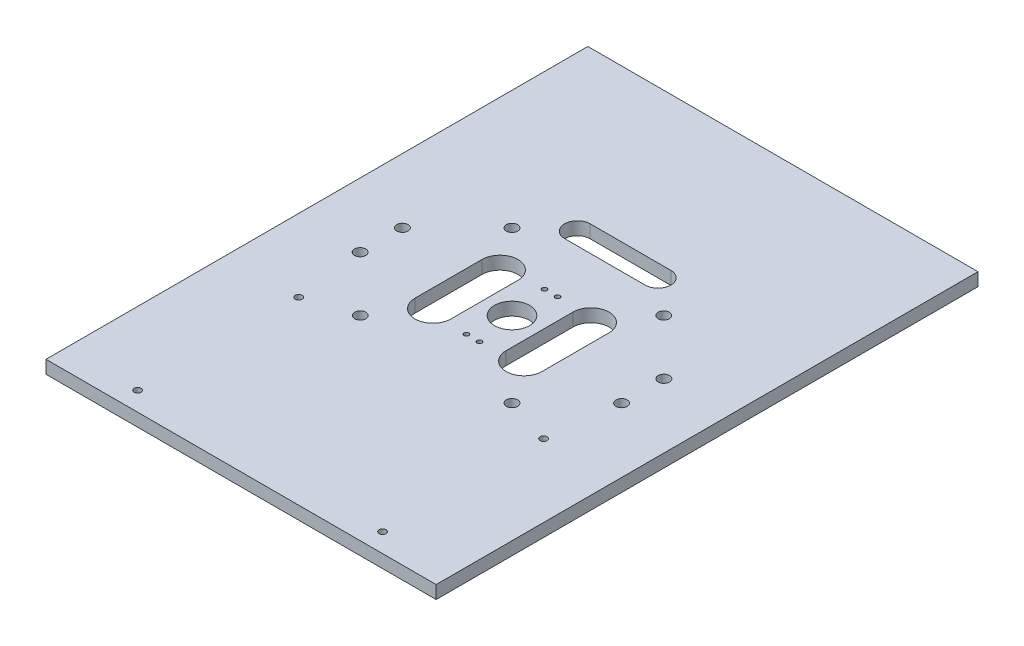
SolidWorks part; units mm, degrees
ref_plane "前视基准面" through (0, 0, 0) normal (0, 0, 1) x (1, 0, 0)
ref_plane "上视基准面" through (0, 0, 0) normal (0, 1, 0) x (1, 0, 0)
ref_plane "右视基准面" through (0, 0, 0) normal (1, 0, 0) x (0, 0, -1)
other "Configuration Table"
sketch "草图1" plane through (0, 0, 0) normal (0, 1, 0) x (1, 0, 0)
  line L1 (40, 40) -> (-40, 40)
  line L2 (40, 40) -> (40, -40)
  line L3 (40, -40) -> (-40, -40)
  line L4 (-40, 40) -> (-40, -40)
  line L5 (40, 40) -> (-40, -40) construction
  line L6 (40, -40) -> (-40, 40) construction
  point P0 (0, 0)
extrude "凸台-拉伸1" add sketch "草图1" along normal blind 2
sketch "草图2" plane through (0, 2, 0) normal (0, 1, 0) x (1, 0, 0)
  line L0 (-40, 40) -> (-33, 40)
  line L1 (40, 40) -> (-40, 40) construction
  line L2 (-40, 40) -> (-40, 33)
  line L3 (-40, 40) -> (-40, -40) construction
  line L4 (40, 40) -> (33, 40)
  line L5 (-40, -40) -> (-40, -33)
  circle A0 centre (-33, 33) radius 2.5
  circle A1 centre (33, 33.941) radius 2.5
  circle A2 centre (-33, -33) radius 2.5
  circle A3 centre (33, -33) radius 2.5
extrude "切除-拉伸1" cut sketch "草图2" against normal blind 2 contours A2 | A0 | A1 | A3
sketch "草图3" plane through (0, 0, 0) normal (0, -1, 0) x (1, 0, 0)
  circle A0 centre (-2.5, 17.5) radius 1
  circle A1 centre (2.5, 17.5) radius 1
  circle A2 centre (-2.5, -17.5) radius 1
  circle A4 centre (2.5, -17.5) radius 1
  point P4 (0, 0)
  point P8 (0, 17.5)
extrude "切除-拉伸2" cut sketch "草图3" against normal blind 2
sketch "草图4" plane through (0, 0, 0) normal (0, -1, 0) x (1, 0, 0)
  circle A0 centre (0, 0) radius 8
extrude "切除-拉伸3" cut sketch "草图4" against normal blind 2
sketch "草图5" plane through (0, 0, 0) normal (0, -1, 0) x (1, 0, 0)
  circle A0 centre (33, 33) radius 2.6
  circle A1 centre (33, -33.941) radius 2.6
  circle A2 centre (-33, -33) radius 2.6
  circle A3 centre (-33, 33) radius 2.6
  circle A4 centre (-2.5, 17.5) radius 1.1
  circle A5 centre (2.5, 17.5) radius 1.1
  circle A6 centre (2.5, -17.5) radius 1.1
  circle A7 centre (-2.5, -17.5) radius 1.1
  dimension "D1" = 5.2
  dimension "D2" = 5.2
  dimension "D3" = 5.2
  dimension "D4" = 5.2
extrude "切除-拉伸4" cut sketch "草图5" against normal blind 10
sketch "草图6" plane through (0, 0, 0) normal (0, -1, 0) x (1, 0, 0)
  line L0 (10.3007, -26.4641) -> (-10.3007, -26.4641) construction
  line L1 (10.3007, -30.5356) -> (-10.3007, -30.5356)
  line L2 (10.3007, -22.3927) -> (-10.3007, -22.3927)
  arc A0 (10.3007, -30.5356) -> (10.3007, -22.3927) centre (10.3007, -26.4641) ccw
  arc A1 (-10.3007, -22.3927) -> (-10.3007, -30.5356) centre (-10.3007, -26.4641) ccw
  point P2 (0, -26.4641)
extrude "切除-拉伸5" cut sketch "草图6" against normal blind 10
sketch "草图7" plane through (0, 0, 0) normal (0, -1, 0) x (1, 0, 0)
  line L1 (62.5, 62.5) -> (-62.5, 62.5)
  line L2 (62.5, 62.5) -> (62.5, -62.5)
  line L3 (62.5, -62.5) -> (-62.5, -62.5)
  line L4 (-62.5, 62.5) -> (-62.5, -62.5)
  line L5 (62.5, 62.5) -> (-62.5, -62.5) construction
  line L6 (62.5, -62.5) -> (-62.5, 62.5) construction
  line L8 (-10.3007, -30.5356) -> (10.3007, -30.5356)
  line L9 (10.3007, -22.3927) -> (-10.3007, -22.3927)
  line L10 (-10.3007, -30.5356) -> (10.3007, -30.5356)
  line L11 (10.3007, -22.3927) -> (-10.3007, -22.3927)
  circle A0 centre (2.5, 17.5) radius 1.1 construction
  circle A1 centre (2.5, 17.5) radius 1.1
  arc A2 (-10.3007, -22.3927) -> (-10.3007, -30.5356) centre (-10.3007, -26.4641) ccw
  arc A3 (10.3007, -30.5356) -> (10.3007, -22.3927) centre (10.3007, -26.4641) ccw
  arc A4 (-10.3007, -22.3927) -> (-10.3007, -30.5356) centre (-10.3007, -26.4641) ccw
  arc A5 (10.3007, -30.5356) -> (10.3007, -22.3927) centre (10.3007, -26.4641) ccw
  circle A6 centre (-2.5, 17.5) radius 1.1 construction
  circle A7 centre (-2.5, 17.5) radius 1.1
  circle A8 centre (-33, -33) radius 2.6 construction
  circle A9 centre (-2.5, -17.5) radius 1.1 construction
  circle A10 centre (2.5, -17.5) radius 1.1 construction
  circle A11 centre (0, 0) radius 8 construction
  circle A12 centre (33, -33.941) radius 2.6 construction
  circle A13 centre (33, 33) radius 2.6 construction
  circle A14 centre (-33, 33) radius 2.6 construction
  circle A15 centre (-33, -33) radius 2.6
  circle A16 centre (-2.5, -17.5) radius 1.1
  circle A17 centre (2.5, -17.5) radius 1.1
  circle A18 centre (0, 0) radius 8
  circle A19 centre (33, -33.941) radius 2.6
  circle A20 centre (33, 33) radius 2.6
  circle A21 centre (-33, 33) radius 2.6
  point P0 (0, 0)
  dimension "D1" = 0
extrude "凸台-拉伸2" add sketch "草图7" against normal blind 2
sketch "草图8" plane through (0, 0, 0) normal (0, -1, 0) x (1, 0, 0)
  line L2 (125, -125) -> (-125, -125)
  line L3 (125, -125) -> (125, 125)
  line L4 (125, 125) -> (-125, 125)
  line L5 (-125, -125) -> (-125, 125)
  line L6 (125, -125) -> (-125, 125) construction
  line L7 (125, 125) -> (-125, -125) construction
  circle A0 centre (2.5, -17.5) radius 1.1 construction
  circle A1 centre (-2.5, -17.5) radius 1.1 construction
  circle A2 centre (-2.5, 17.5) radius 1.1 construction
  circle A3 centre (2.5, 17.5) radius 1.1 construction
  circle A4 centre (0, 0) radius 8 construction
  circle A5 centre (2.5, -17.5) radius 1.1
  circle A6 centre (-2.5, -17.5) radius 1.1
  circle A7 centre (-2.5, 17.5) radius 1.1
  circle A8 centre (2.5, 17.5) radius 1.1
  circle A9 centre (0, 0) radius 8
  point P0 (0, 0)
  point P3 (0, 50.3246)
extrude "凸台-拉伸4" add sketch "草图8" against normal blind 2
sketch "草图11" plane through (0, 0, 0) normal (0, -1, 0) x (1, 0, 0)
  line L0 (0, 0) -> (0, -40.4625)
  line L1 (25, -40.4625) -> (-25, -40.4625) construction
  line L2 (25, -55.4625) -> (-25, -55.4625)
  line L3 (25, -25.4625) -> (-25, -25.4625)
  arc A0 (25, -55.4625) -> (25, -25.4625) centre (25, -40.4625) ccw
  arc A1 (-25, -25.4625) -> (-25, -55.4625) centre (-25, -40.4625) ccw
  point P5 (0, -40.4625)
extrude "切除-拉伸7" cut sketch "草图11" against normal blind 70
sketch "草图13" plane through (0, 0, 0) normal (0, -1, 0) x (1, 0, 0)
  line L0 (-125, 125) -> (-105, 125)
  line L1 (125, 125) -> (-125, 125) construction
  line L2 (-125, 125) -> (-125, 105)
  line L3 (-125, 125) -> (-125, -125) construction
  line L4 (125, 125) -> (105, 125)
  line L5 (-125, -125) -> (-125, -105)
  circle A0 centre (-105, 105) radius 2.6
  circle A1 centre (105, 105) radius 2.6
  circle A2 centre (-105, -105) radius 2.6
  circle A3 centre (105, -105) radius 2.6
  dimension "D1" = 5.2
  dimension "D2" = 5.2
  dimension "D3" = 5.2
  dimension "D4" = 5.2
extrude "切除-拉伸10" cut sketch "草图13" against normal blind 61.5 contours A2 | A0 | A1 | A3
sketch "草图14" plane through (0, 0, 0) normal (0, -1, 0) x (1, 0, 0)
  line L0 (25, -55.4625) -> (-25, -55.4625) construction
  line L1 (25, -25.4625) -> (-25, -25.4625) construction
  line L2 (25, -55.4625) -> (-25, -55.4625)
  line L3 (25, -25.4625) -> (-25, -25.4625)
  arc A0 (25, -55.4625) -> (25, -25.4625) centre (25, -40.4625) ccw construction
  arc A1 (-25, -25.4625) -> (-25, -55.4625) centre (-25, -40.4625) ccw construction
  arc A2 (25, -55.4625) -> (25, -25.4625) centre (25, -40.4625) ccw
  arc A3 (-25, -25.4625) -> (-25, -55.4625) centre (-25, -40.4625) ccw
extrude "凸台-拉伸5" add sketch "草图14" against normal blind 2
sketch "草图16" plane through (0, 0, 0) normal (0, -1, 0) x (-1, 0, 0)
  line L0 (-21, 15.4495) -> (-21, -15.4495) construction
  line L1 (-12.6913, 15.4495) -> (-12.6913, -15.4495)
  line L2 (-29.3087, 15.4495) -> (-29.3087, -15.4495)
  line L3 (21, -15.4495) -> (21, 15.4495) construction
  line L4 (12.6913, -15.4495) -> (12.6913, 15.4495)
  line L5 (29.3087, -15.4495) -> (29.3087, 15.4495)
  arc A1 (-12.6913, 15.4495) -> (-29.3087, 15.4495) centre (-21, 15.4495) ccw
  arc A2 (-29.3087, -15.4495) -> (-12.6913, -15.4495) centre (-21, -15.4495) ccw
  arc A3 (12.6913, -15.4495) -> (29.3087, -15.4495) centre (21, -15.4495) ccw
  arc A4 (29.3087, 15.4495) -> (12.6913, 15.4495) centre (21, 15.4495) ccw
  point P5 (-21, 0)
  point P14 (21, 0)
  point P19 (0, 0)
  dimension "D2" = 2
extrude "切除-拉伸12" cut sketch "草图16" against normal blind 2 contours L4 A4 L5 A3 | L2 A2 L1 A1
sketch "草图17" plane through (0, 0, 0) normal (0, -1, 0) x (1, 0, 0)
  line L0 (0, -18) -> (0, 18)
  circle A0 centre (2.5, -17.5) radius 1.1 construction
  circle A1 centre (-2.5, -17.5) radius 1.1 construction
  circle A2 centre (2.5, 17.5) radius 1.1 construction
  circle A3 centre (-2.5, 17.5) radius 1.1 construction
  circle A4 centre (2.5, -17.5) radius 1.1
  circle A5 centre (-2.5, -17.5) radius 1.1
  circle A6 centre (2.5, 17.5) radius 1.1
  circle A7 centre (-2.5, 17.5) radius 1.1
  point P5 (0, 0)
extrude "凸台-拉伸6" add sketch "草图17" against normal blind 2 contours A6 | A7 | A5 | A4
sketch "草图18" plane through (0, 0, 0) normal (0, -1, 0) x (1, 0, 0)
  line L0 (0, -18) -> (0, 18)
  line L1 (3, 18) -> (-3, 18)
  circle A0 centre (3, 18) radius 1.1
  circle A1 centre (-3, 18) radius 1.1
  circle A2 centre (-3, -18) radius 1.1
  circle A3 centre (3, -18) radius 1.1
  point P5 (0, 0)
  point P8 (0, 18)
  dimension "D1" = 2.2
  dimension "D2" = 2.2
  dimension "D3" = 2.2
  dimension "D4" = 2.2
extrude "切除-拉伸13" cut sketch "草图18" against normal blind 2 contours A1 | A0 | A2 | A3
sketch "草图19" plane through (0, 0, 0) normal (0, -1, 0) x (1, 0, 0)
  line L1 (35, -35) -> (-35, -35)
  line L2 (35, -35) -> (35, 35)
  line L3 (35, 35) -> (-35, 35)
  line L5 (35, -35) -> (-35, 35) construction
  line L6 (35, 35) -> (-35, -35) construction
  circle A0 centre (-35, 35) radius 2.6
  circle A1 centre (35, 34.4348) radius 2.6
  circle A2 centre (35, -35) radius 2.6
  circle A3 centre (-35, -35) radius 2.6
  point P0 (0, 0)
  dimension "D1" = 5.2
  dimension "D2" = 5.2
  dimension "D3" = 5.2
  dimension "D4" = 5.2
sketch "草图20" plane through (0, 0, 0) normal (0, -1, 0) x (1, 0, 0)
  line L0 (60.05, 119.2228) -> (-60.05, 119.2228)
  line L1 (-60.05, 119.2228) -> (-60.05, 38.9228)
  line L2 (-60.05, 38.9228) -> (60.05, 38.9228)
  line L3 (60.05, 38.9228) -> (60.05, 119.2228)
  point P3 (0, 119.2228)
  dimension "D1" = 120.1
extrude "切除-拉伸14" cut sketch "草图20" against normal blind 0.5
sketch "草图21" plane through (0, 0.5, 0) normal (0, -1, 0) x (1, 0, 0)
  line L0 (0, 116.2228) -> (0, 41.9228)
  line L3 (56.5, 79.0728) -> (-56.5, 79.0728)
  circle A0 centre (-56.5, 116.2228) radius 1.6
  circle A1 centre (56.5, 116.2228) radius 1.6
  circle A2 centre (56.5, 41.9228) radius 1.6
  circle A3 centre (-56.5, 41.9228) radius 1.6
  point P3 (0, 79.0728)
  point P9 (0, 79.0728)
  dimension "D1" = 3.2
  dimension "D2" = 3.2
  dimension "D3" = 3.2
  dimension "D4" = 3.2
extrude "切除-拉伸15" cut sketch "草图21" against normal blind 10 contours A0 | A3 | A1 | A2
extrude "切除-拉伸16" cut sketch "草图19" against normal blind 10
sketch "草图22" plane through (0, 0, 0) normal (0, -1, 0) x (1, 0, 0)
  line L0 (67.5, 0) -> (-67.5, 0)
  line L1 (-67.5, -125) -> (-67.5, 125)
  line L2 (-125, -125) -> (125, -125) construction
  line L3 (125, 125) -> (-125, 125) construction
  line L4 (-67.5, 125) -> (-125, 125)
  line L5 (-125, 125) -> (-125, -125)
  line L6 (-125, 125) -> (-125, -125) construction
  line L7 (-125, -125) -> (-67.5, -125)
  line L8 (67.5, -121.8944) -> (67.5, 125)
  line L9 (67.5, 125) -> (125, 125)
  line L10 (125, 125) -> (125, -125)
  line L11 (67.5, -121.8944) -> (67.5, -125)
  line L12 (67.5, -125) -> (125, -125)
  line L13 (-67.5, -102.7475) -> (67.5, -102.7475)
  line L14 (-67.5, -125) -> (67.5, -125)
  line L18 (18.5971, -48.7725) -> (-18.5971, -48.7725) construction
  line L19 (18.5971, -54.6789) -> (-18.5971, -54.6789)
  line L20 (18.5971, -42.8662) -> (-18.5971, -42.8662)
  arc A2 (18.5971, -54.6789) -> (18.5971, -42.8662) centre (18.5971, -48.7725) ccw
  arc A3 (-18.5971, -42.8662) -> (-18.5971, -54.6789) centre (-18.5971, -48.7725) ccw
  point P5 (0, 0)
  point P32 (0, -48.7725)
sketch "草图24" plane through (0, 0, 0) normal (0, -1, 0) x (1, 0, 0)
  circle A0 centre (0, 0) radius 8.1
extrude "切除-拉伸19" cut sketch "草图24" against normal blind 10
extrude "切除-拉伸20" cut sketch "草图22" against normal blind 10
sketch "草图25" plane through (0, 0, 0) normal (0, -1, 0) x (-1, 0, 0)
  line L0 (29.3087, 0) -> (60.3087, 0)
  line L1 (29.3087, -15.4495) -> (29.3087, 15.4495) construction
  line L2 (60.3087, 9.5) -> (60.3087, -9.5)
  line L3 (-29.3087, 0) -> (-60.3087, 0)
  line L4 (-29.3087, 15.4495) -> (-29.3087, -15.4495) construction
  line L5 (-60.3087, 9) -> (-60.3087, -9)
  line L6 (-75, 125) -> (75, 125)
  line L7 (125, 125) -> (-125, 125) construction
  line L8 (75, 125) -> (125, 125)
  line L9 (125, -125) -> (125, 125) construction
  line L10 (125, 125) -> (125, -125)
  line L11 (125, -125) -> (75, -125)
  line L12 (-125, -125) -> (125, -125) construction
  line L13 (75, -125) -> (75, 125)
  line L14 (-75, 125) -> (-125, 125)
  line L15 (-125, 125) -> (-125, -125)
  line L16 (-75, 125) -> (-75, -125)
  line L17 (-75, -125) -> (-125, -125)
  circle A0 centre (60.3087, -9.5) radius 2.6
  circle A1 centre (60.3087, 9.5) radius 2.6
  circle A2 centre (-60.3087, -9) radius 2.6
  circle A3 centre (-60.3087, 9) radius 2.6
  point P8 (60.3087, 0)
  point P15 (-60.3087, 0)
  point P20 (0, 125)
  dimension "D1" = 5.2
  dimension "D2" = 5.2
  dimension "D3" = 5.2
  dimension "D4" = 5.2
extrude "切除-拉伸21" cut sketch "草图25" against normal blind 18
sketch "草图29" plane through (0, 0, 0) normal (0, -1, 0) x (-1, 0, 0)
  line L0 (-75, -125) -> (-90, -125)
  line L1 (-90, -125) -> (-90, 125)
  line L2 (-90, 125) -> (-75, 125)
  line L3 (-75, 125) -> (-75, -125) construction
  line L4 (-75, 125) -> (-75, -125)
  line L5 (75, -125) -> (90, -125)
  line L6 (-75, -125) -> (75, -125) construction
  line L7 (75, -125) -> (75, 125) construction
  line L8 (90, -125) -> (90, 125)
  line L9 (90, 125) -> (75, 125)
  line L10 (75, 125) -> (78.6, 125)
  line L11 (75, -125) -> (75, 125)
  line M36 (75, -125) -> (75, 125)
  line M38 (-75, 125) -> (-75, -125)
extrude "凸台-拉伸9" add sketch "草图29" along direction (0, -1, 0) on the side against the normal up to surface (2 mm away) contours L8 L9 L5 M36 | L2 L1 L0 M38
sketch "草图31" plane through (0, 2, 0) normal (0, 1, 0) x (1, 0, 0)
  line L0 (-29.3087, -15.4495) -> (-29.3087, 15.4495) construction
  line L1 (-90, -125) -> (90, -125)
  line L2 (-90, -125) -> (-90, 125)
  line L3 (-90, 125) -> (90, 125)
  line L4 (90, -125) -> (90, 125)
  line L5 (-90, -125) -> (90, 125) construction
  line L6 (-90, 125) -> (90, -125) construction
  line L7 (-12.6913, -15.4495) -> (-12.6913, 15.4495) construction
  line L8 (18.5971, 54.6789) -> (-18.5971, 54.6789) construction
  line L9 (18.5971, 42.8662) -> (-18.5971, 42.8662) construction
  line L10 (-29.3087, -15.4495) -> (-29.3087, 15.4495)
  line L11 (-12.6913, -15.4495) -> (-12.6913, 15.4495)
  line L12 (18.5971, 54.6789) -> (-18.5971, 54.6789)
  line L13 (18.5971, 42.8662) -> (-18.5971, 42.8662)
  circle A0 centre (-56.5, -116.2228) radius 1.6 construction
  circle A1 centre (56.5, -116.2228) radius 1.6 construction
  circle A2 centre (56.5, -41.9228) radius 1.6 construction
  circle A3 centre (35, -34.4348) radius 2.6 construction
  circle A4 centre (60.3087, -9) radius 2.6 construction
  circle A5 centre (60.3087, 9) radius 2.6 construction
  circle A6 centre (35, 35) radius 2.6 construction
  circle A7 centre (3, -18) radius 1.1 construction
  circle A8 centre (-3, -18) radius 1.1 construction
  circle A9 centre (-3, 18) radius 1.1 construction
  circle A10 centre (3, 18) radius 1.1 construction
  arc A11 (-12.6913, 15.4495) -> (-29.3087, 15.4495) centre (-21, 15.4495) ccw construction
  arc A12 (-29.3087, -15.4495) -> (-12.6913, -15.4495) centre (-21, -15.4495) ccw construction
  circle A13 centre (0, 0) radius 8.1 construction
  circle A14 centre (-35, -35) radius 2.6 construction
  circle A15 centre (-56.5, -41.9228) radius 1.6 construction
  circle A16 centre (-60.3087, -9.5) radius 2.6 construction
  circle A17 centre (-60.3087, 9.5) radius 2.6 construction
  circle A18 centre (-35, 35) radius 2.6 construction
  arc A19 (-18.5971, 54.6789) -> (-18.5971, 42.8662) centre (-18.5971, 48.7725) ccw construction
  arc A20 (18.5971, 42.8662) -> (18.5971, 54.6789) centre (18.5971, 48.7725) ccw construction
  circle A21 centre (-56.5, -116.2228) radius 1.6
  circle A22 centre (56.5, -116.2228) radius 1.6
  circle A23 centre (56.5, -41.9228) radius 1.6
  circle A24 centre (35, -34.4348) radius 2.6
  circle A25 centre (60.3087, -9) radius 2.6
  circle A26 centre (60.3087, 9) radius 2.6
  circle A27 centre (35, 35) radius 2.6
  circle A28 centre (3, -18) radius 1.1
  circle A29 centre (-3, -18) radius 1.1
  circle A30 centre (-3, 18) radius 1.1
  circle A31 centre (3, 18) radius 1.1
  arc A32 (-12.6913, 15.4495) -> (-29.3087, 15.4495) centre (-21, 15.4495) ccw
  arc A33 (-29.3087, -15.4495) -> (-12.6913, -15.4495) centre (-21, -15.4495) ccw
  circle A34 centre (0, 0) radius 8.1
  circle A35 centre (-35, -35) radius 2.6
  circle A36 centre (-56.5, -41.9228) radius 1.6
  circle A37 centre (-60.3087, -9.5) radius 2.6
  circle A38 centre (-60.3087, 9.5) radius 2.6
  circle A39 centre (-35, 35) radius 2.6
  arc A40 (-18.5971, 54.6789) -> (-18.5971, 42.8662) centre (-18.5971, 48.7725) ccw
  arc A41 (18.5971, 42.8662) -> (18.5971, 54.6789) centre (18.5971, 48.7725) ccw
  point P0 (0, 0)
extrude "凸台-拉伸10" add sketch "草图31" along normal blind 4
sketch "草图32" plane through (0, 2, 0) normal (0, -1, 0) x (1, 0, 0)
  line L0 (21, 23.7582) -> (21, -23.7582)
  line L1 (12.6913, -15.4495) -> (12.6913, 15.4495) construction
  line L2 (29.3087, -15.4495) -> (29.3087, 15.4495) construction
  line L3 (12.6913, -15.4495) -> (12.6913, 15.4495)
  line L4 (29.3087, -15.4495) -> (29.3087, 15.4495)
  arc A0 (29.3087, 15.4495) -> (12.6913, 15.4495) centre (21, 15.4495) ccw construction
  arc A1 (12.6913, -15.4495) -> (29.3087, -15.4495) centre (21, -15.4495) ccw construction
  arc A2 (12.6913, -15.4495) -> (29.3087, -15.4495) centre (21, -15.4495) ccw
  arc A3 (29.3087, 15.4495) -> (12.6913, 15.4495) centre (21, 15.4495) ccw
  arc M2 (12.6913, -15.4495) -> (29.3087, -15.4495) centre (21, -15.4495) ccw
  line M3 (29.3087, -15.4495) -> (29.3087, 15.4495)
  arc M4 (29.3087, 15.4495) -> (12.6913, 15.4495) centre (21, 15.4495) ccw
  line M5 (12.6913, 15.4495) -> (12.6913, -15.4495)
extrude "切除-拉伸22" cut sketch "草图32" against normal blind 56 contours L0 M4 M2 M3 | L0 M4 M5 M2
sketch "草图33" plane through (0, 0, 0) normal (0, -1, 0) x (1, 0, 0)
  circle A0 centre (-35, 35) radius 2.6
  circle A1 centre (35, 34.4348) radius 2.6
extrude "凸台-拉伸11" add sketch "草图33" against normal up to surface (6 mm away) up to face at (21, 6, 0)
sketch "草图34" plane through (0, 0, 0) normal (0, -1, 0) x (1, 0, 0)
  line L0 (35, -35) -> (35, 35)
  line L1 (-35, -35) -> (-35, 35)
  circle A0 centre (-35, 35) radius 2.6
  circle A1 centre (35, 35) radius 2.6
extrude "切除-拉伸23" cut sketch "草图34" against normal blind 10
sketch "草图35" plane through (0, 0, 0) normal (0, -1, 0) x (1, 0, 0)
  circle A0 centre (-60.3087, 9.5) radius 2.6
  circle A1 centre (-60.3087, -9.5) radius 2.6
  circle A2 centre (60.3087, 9) radius 2.6
  circle A3 centre (60.3087, -9) radius 2.6
extrude "凸台-拉伸12" add sketch "草图35" against normal up to surface (6 mm away)
sketch "草图36" plane through (0, 0, 0) normal (0, -1, 0) x (1, 0, 0)
  line L0 (-29.3087, 0) -> (-60.3087, 0)
  line L1 (-29.3087, 15.4495) -> (-29.3087, -15.4495) construction
  line L2 (-60.3087, -9.75) -> (-60.3087, 9.75)
  line L3 (29.3087, -15.4495) -> (29.3087, 15.4495) construction
  line L4 (29.3087, 0) -> (60.3087, 0)
  line L5 (60.3087, -9.75) -> (60.3087, 9.75)
  circle A0 centre (-60.3087, 9.75) radius 2.6
  circle A1 centre (-60.3087, -9.75) radius 2.6
  circle A2 centre (60.3087, 9.75) radius 2.6
  circle A3 centre (60.3087, -9.75) radius 2.6
  point P8 (-60.3087, 0)
  point P16 (60.3087, 0)
extrude "切除-拉伸24" cut sketch "草图36" against normal blind 20
